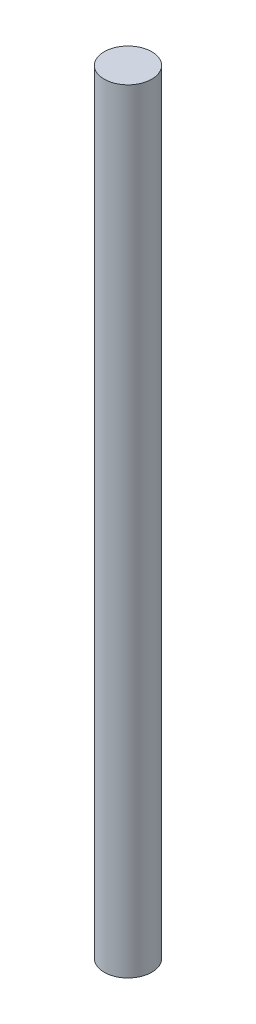
SolidWorks part; units mm, degrees
material "Plain Carbon Steel"
ref_plane "Front Plane" through (0, 0, 0) normal (0, 0, 1) x (1, 0, 0)
ref_plane "Top Plane" through (0, 0, 0) normal (0, 1, 0) x (1, 0, 0)
ref_plane "Right Plane" through (0, 0, 0) normal (1, 0, 0) x (0, 0, -1)
sketch "Sketch1" plane through (0, 0, 0) normal (0, 1, 0) x (1, 0, 0)
  circle A0 centre (0, 0) radius 4
  dimension "D1" = 8
extrude "Boss-Extrude1" add sketch "Sketch1" against normal blind 130
